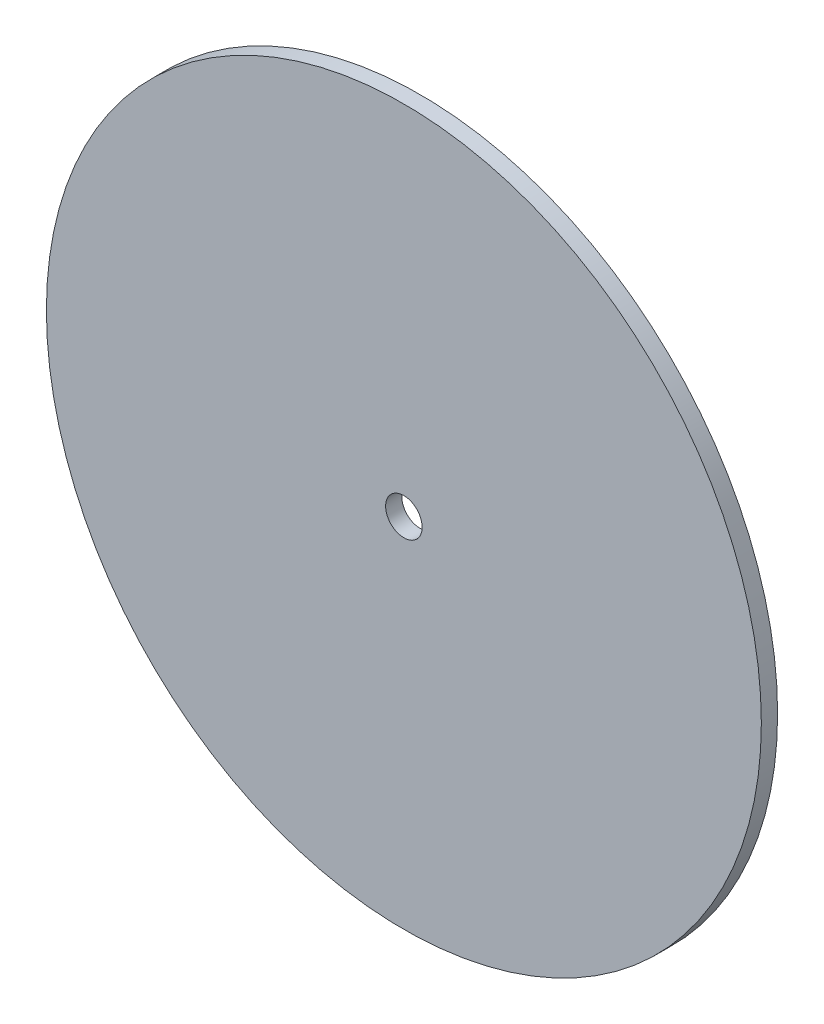
SolidWorks part; units mm, degrees
material "5052-H38"
ref_plane "Front Plane" through (0, 0, 0) normal (0, 0, 1) x (1, 0, 0)
ref_plane "Top Plane" through (0, 0, 0) normal (0, 1, 0) x (1, 0, 0)
ref_plane "Right Plane" through (0, 0, 0) normal (1, 0, 0) x (0, 0, -1)
sketch "Sketch2" plane through (0, 0, 0) normal (0, 0, 1) x (1, 0, 0)
  circle A0 centre (0, 0) radius 279.4
  circle A1 centre (0, 0) radius 14.2875
  dimension "D1" = 558.8
  dimension "D2" = 28.575
extrude "Boss-Extrude1" add sketch "Sketch2" along normal blind 12.7
